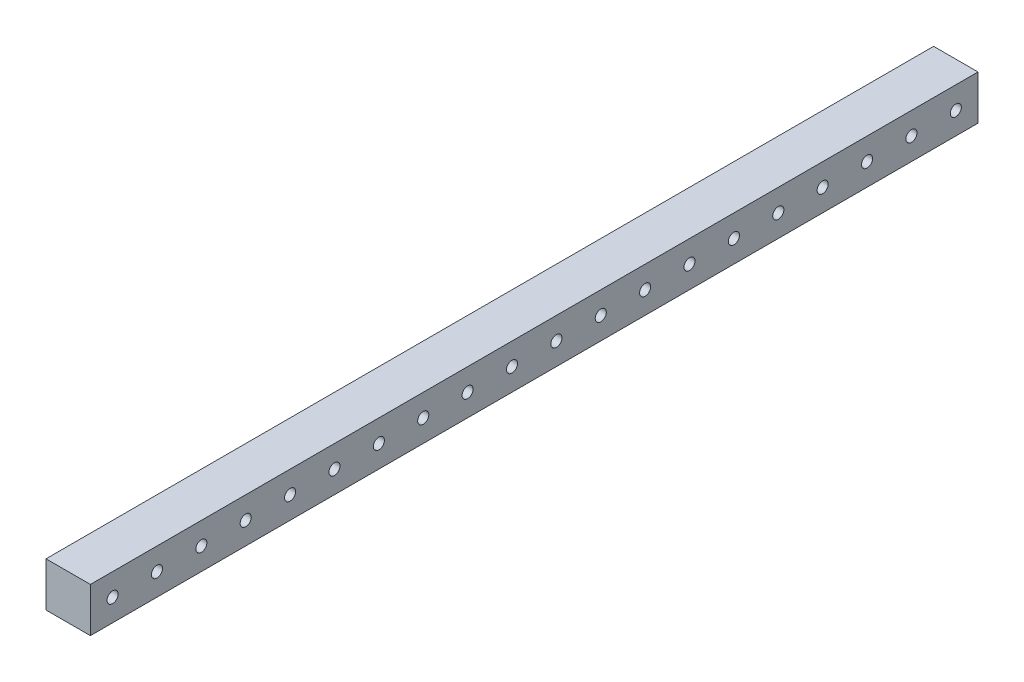
SolidWorks part; units mm, degrees
material "Pine"
ref_plane "Front Plane" through (0, 0, 0) normal (0, 0, 1) x (1, 0, 0)
ref_plane "Top Plane" through (0, 0, 0) normal (0, 1, 0) x (1, 0, 0)
ref_plane "Right Plane" through (0, 0, 0) normal (1, 0, 0) x (0, 0, -1)
sketch "Sketch1" plane through (0, 0, 0) normal (0, 0, 1) x (1, 0, 0)
  line L0 (-10, -10) -> (10, 10) construction
  line L1 (-10, 10) -> (10, 10)
  line L2 (-10, 10) -> (-10, -10)
  line L3 (-10, -10) -> (10, -10)
  line L4 (10, 10) -> (10, -10)
  point P4 (0, 0)
  dimension "D1" = 20
  dimension "D2" = 45
extrude "Boss-Extrude1" add sketch "Sketch1" along normal blind 400
hole_wizard "Ø5.0mm Dowel Hole1" positions "Sketch2" profile "Sketch3" hole size "Ø5.0" standard "ANSI Metric" end condition through all
sketch "Sketch2" plane through (10, 0, 0) normal (1, 0, 0) x (0, 0, -1)
  line L0 (0, -10) -> (0, 10) construction
  point P0 (-10, 0)
  point P7 (0, 0)
  dimension "D1" = 10
sketch "Sketch3" plane through (10, 0, 10) normal (0, 1, 0) x (0, 0, -1)
  line L0 (0, 0) -> (0, 20)
  line L1 (0, 20) -> (2.5, 20)
  line L2 (2.5, 20) -> (2.5, 0)
  line L5 (2.5, 0) -> (0, 0)
  line L11 (0, -6.35) -> (0, 107.95) construction
  dimension "Thru Hole Dia." = 5
  dimension "Thru Hole Depth" = 20
pattern_linear "LPattern2" count 20 spacing 20 along (0, 0, 1) of "Ø5.0mm Dowel Hole1"
